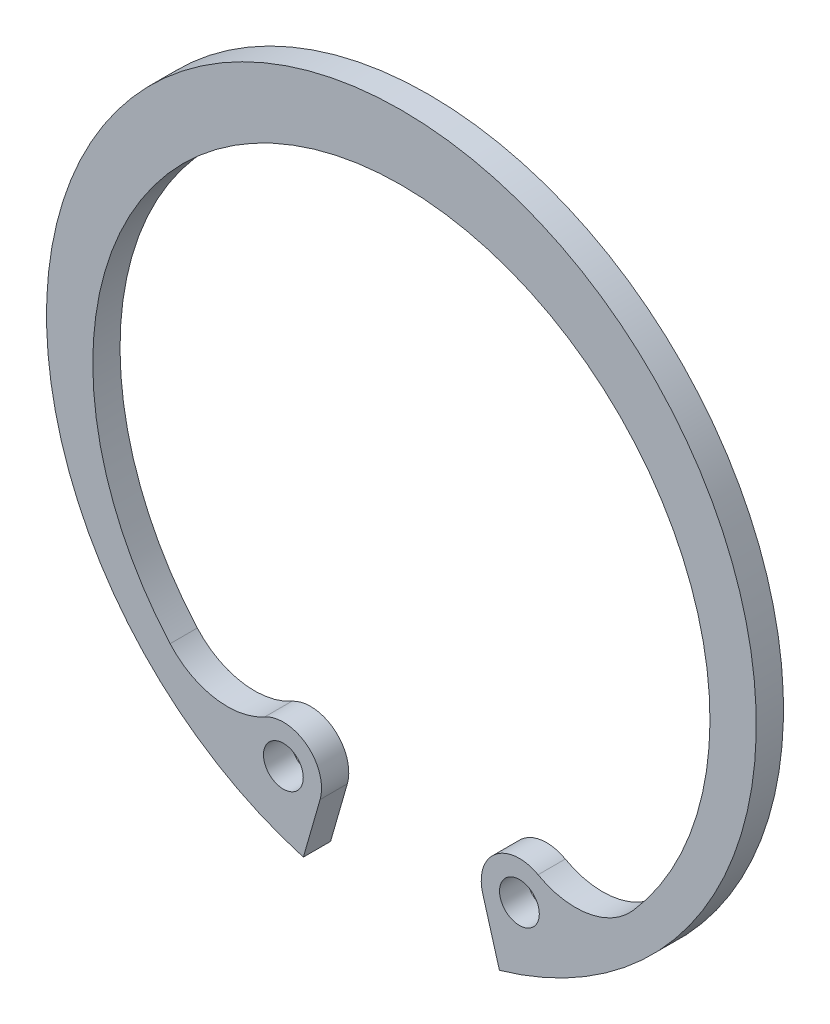
SolidWorks part; units mm, degrees
extrude "Body" add sketch "BodySke" against normal blind 1.3
sketch "BodySke" plane through (0, 0, 0) normal (0, 0, 1) x (1, 0, 0)
  line L0 (-1.5431, 0) -> (1.5431, 0) construction
  line L1 (0, 0) -> (0, 13.85) construction
  line L2 (4.6821, -16.2905) -> (3.883, -13.5101)
  line L3 (-4.6821, -16.2905) -> (-3.883, -13.5101)
  line L4 (0, 0) -> (12.0453, -11.9254) construction
  line L5 (0, 0) -> (-12.0453, -11.9254) construction
  line L6 (-5.3746, -12.0929) -> (-5.8994, -13.919) construction
  line L7 (5.4296, -12.2846) -> (5.8443, -13.7273) construction
  arc A0 (-3.883, -13.5101) -> (-6.5284, -11.4135) centre (-5.637, -13.006) ccw
  arc A1 (6.5284, -11.4135) -> (3.883, -13.5101) centre (5.637, -13.006) ccw
  arc A2 (10.9082, -10.7997) -> (-10.9082, -10.7997) centre (0, -0.8885) ccw construction
  arc A3 (4.6821, -16.2905) -> (-4.6821, -16.2905) centre (0, 0) ccw
  circle A4 centre (5.637, -13.006) radius 0.95
  circle A5 centre (-5.637, -13.006) radius 0.95
  arc A7 (11.0471, -10.6447) -> (-11.0471, -10.6447) centre (0, -0.8885) ccw
  arc A8 (-5.637, -13.006) -> (5.637, -13.006) centre (0, 0) ccw construction
  arc A9 (-11.0471, -10.6447) -> (-6.5284, -11.4135) centre (-8.3113, -8.2285) ccw
  arc A10 (6.5284, -11.4135) -> (11.0471, -10.6447) centre (8.3113, -8.2285) ccw
  dimension "HoleOffsetRad" = 4.075
  dimension "TipRad" = 0.925
  dimension "HoleDia" = 1
  dimension "FilletRad" = 1.85
  dimension "LargeRad" = 3.95
  dimension "SmallRad" = 4.55
  dimension "GapAngle" = 29.143
ref_plane "Plane1" through (0, 0, 0) normal (0, 0, 1) x (1, 0, 0)
ref_plane "Plane2" through (0, 0, 0) normal (0, 1, 0) x (1, 0, 0)
ref_plane "Plane3" through (0, 0, 0) normal (1, 0, 0) x (0, 0, -1)
other "Configuration Table"
sketch "Clipboard" plane through (0, 0, 0) normal (0, 0, 1) x (1, 0, 0)
  line L0 (0, 0) -> (3.1, 0)
  line L1 (0, 0) -> (0, 1.6)
  line L2 (0, 0) -> (0, -4.6)
  circle A0 centre (0, 0) radius 0.95
  circle A1 centre (0, 0) radius 16
sketch "ModLugSke" plane through (0, 0, 0) normal (0, 0, 1) x (1, 0, 0)
  line L0 (4.6821, -16.2905) -> (3.6645, -12.7499)
  line L1 (-4.6821, -16.2905) -> (-3.6645, -12.7499)
  line L2 (8.8183, -8.6464) -> (12.1028, -11.867) construction
  line L3 (-8.8183, -8.6464) -> (-12.1028, -11.867) construction
  line L4 (-4.6821, -16.2905) -> (-3.883, -13.5101) construction
  line L5 (3.883, -13.5101) -> (4.6821, -16.2905) construction
  line L6 (0, 0) -> (0, -12.7358) construction
  line L7 (10.9556, -10.7421) -> (12.1028, -11.867)
  line L8 (-12.1028, -11.867) -> (-10.9556, -10.7421)
  arc A0 (4.6821, -16.2905) -> (12.1028, -11.867) centre (0, 0) ccw
  arc A1 (-5.872, -10.8647) -> (-4.2506, -11.5955) centre (0, 0) ccw
  arc A2 (4.6821, -16.2905) -> (-4.6821, -16.2905) centre (0, 0) ccw construction
  arc A3 (6.5284, -11.4135) -> (3.883, -13.5101) centre (5.637, -13.006) ccw construction
  arc A4 (-5.872, -10.8647) -> (-6.9247, -10.9647) centre (-6.3237, -11.7005) ccw
  arc A5 (-10.9556, -10.7421) -> (-6.9247, -10.9647) centre (-8.8183, -8.6464) ccw
  arc A6 (11.0471, -10.6447) -> (-11.0471, -10.6447) centre (0, -0.8885) ccw construction
  arc A7 (6.9247, -10.9647) -> (10.9556, -10.7421) centre (8.8183, -8.6464) ccw
  arc A8 (4.2506, -11.5955) -> (5.872, -10.8647) centre (0, 0) ccw
  arc A9 (-12.1028, -11.867) -> (-4.6821, -16.2905) centre (0, 0) ccw
  circle A10 centre (-5.637, -13.006) radius 0.95
  circle A11 centre (-5.637, -13.006) radius 0.95 construction
  circle A12 centre (5.637, -13.006) radius 0.95
  circle A13 centre (5.637, -13.006) radius 0.95 construction
  arc A14 (-4.2506, -11.5955) -> (-3.6645, -12.7499) centre (-4.5775, -12.4874) cw
  arc A15 (4.2506, -11.5955) -> (3.6645, -12.7499) centre (4.5775, -12.4874) ccw
  arc A16 (5.872, -10.8647) -> (6.9247, -10.9647) centre (6.3237, -11.7005) cw
  point P43 (3.4115, -11.8695)
extrude "ModLug" [suppressed] add sketch "ModLugSke" against normal through all
equation "' \"BoreDia@Clipboard\" = 8"
equation "' \"Thickness@Body\" = 0.4"
equation "' \"GrooveDia@BodySke\" = 8.4"
equation "' \"LugSection@Clipboard\" = 1.7"
equation "' \"LargeSection@Clipboard\" = 0.85"
equation "' \"SmallSection@Clipboard\" = 0.45"
equation "' \"HoleDia@Clipboard\" = 0.8"
equation "' \"BoreDia@Clipboard\" = 25"
equation "' \"Thickness@Body\" = 1.1"
equation "' \"GrooveDia@BodySke\" = 26.6"
equation "' \"LugSection@Clipboard\" = 4"
equation "' \"LargeSection@Clipboard\" = 2.6"
equation "' \"SmallSection@Clipboard\" = 1.3"
equation "' \"HoleDia@Clipboard\" = 1.5"
equation "\"TipRad@BodySke\" = (\"LugSection@Clipboard\" - (\"GrooveDia@BodySke\" / 2  -  \"BoreDia@Clipboard\" / 2 ) ) / 2"
equation "\"HoleOffsetRad@BodySke\" = (\"GrooveDia@BodySke\" / 2) - \"LugSection@Clipboard\"  + \"TipRad@BodySke\""
equation "\"LargeRad@BodySke\" =  \"GrooveDia@BodySke\" / 2 -  \"LargeSection@Clipboard\""
equation "\"SmallRad@BodySke\" =  \"GrooveDia@BodySke\" / 2 -  \"SmallSection@Clipboard\""
equation "\"HoleDia@BodySke\" =  \"HoleDia@Clipboard\""
equation "\"FilletRad@BodySke\" = \"TipRad@BodySke\" * 2"
equation "\"GapAngle@BodySke\" = 360 - 0.965 * 360 * ( \"BoreDia@Clipboard\" /  \"GrooveDia@BodySke\")"
equation "\"LugAng@ModLugSke\" = \"GapAngle@BodySke\"  + 1.5 * 360 * (\"LugSection@Clipboard\" / (\"BoreDia@Clipboard\" * 3.1416))"
